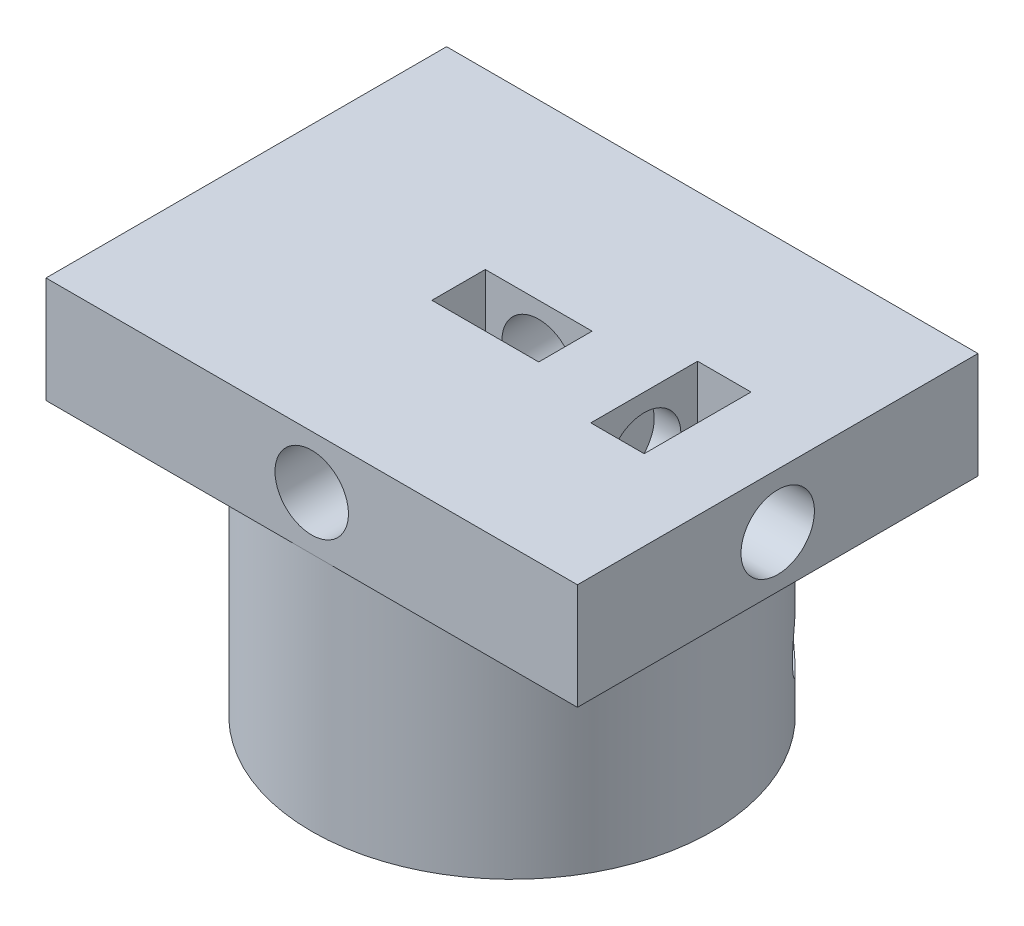
SolidWorks part; units mm, degrees
material "ONYX"
ref_plane "Front Plane" through (0, 0, 0) normal (0, 0, 1) x (1, 0, 0)
ref_plane "Top Plane" through (0, 0, 0) normal (0, 1, 0) x (1, 0, 0)
ref_plane "Right Plane" through (0, 0, 0) normal (1, 0, 0) x (0, 0, -1)
sketch "Sketch1" plane through (0, 0, 0) normal (0, 1, 0) x (1, 0, 0)
  circle A0 centre (0, 0) radius 4.5
  circle A1 centre (0, 0) radius 15
  dimension "D1" = 9
  dimension "D2" = 30
extrude "Boss-Extrude1" add sketch "Sketch1" along normal mid plane 18
sketch "Sketch2" plane through (0, 9, 0) normal (0, 1, 0) x (1, 0, 0)
  line L1 (19.9, -15) -> (-19.9, -15)
  line L2 (19.9, -15) -> (19.9, 15)
  line L3 (19.9, 15) -> (-19.9, 15)
  line L4 (-19.9, -15) -> (-19.9, 15)
  line L5 (19.9, -15) -> (-19.9, 15) construction
  line L6 (19.9, 15) -> (-19.9, -15) construction
  point P0 (0, 0)
  dimension "D1" = 30
  dimension "D2" = 39.8
extrude "Boss-Extrude2" add sketch "Sketch2" along normal blind 7.95
sketch "Sketch3" plane through (0, 0, -15) normal (0, 0, -1) x (-1, 0, 0)
  line L1 (-19.9, 12.975) -> (19.9, 12.975) construction
  line L2 (19.9, 16.95) -> (19.9, 9) construction
  line L3 (-19.9, 16.95) -> (-19.9, 9) construction
  line L4 (0, 16.95) -> (0, 9) construction
  line L5 (-19.9, 16.95) -> (19.9, 16.95) construction
  circle A0 centre (0, 12.975) radius 2.75
  dimension "D3" = 5.5
ref_plane "Plane1" through (0, 0, 0) normal (0.7071, 0, -0.7071) x (-0.7071, 0, -0.7071)
ref_plane "Plane2" through (0, 0, 0) normal (0.7071, 0, 0.7071) x (0.7071, 0, -0.7071)
ref_plane "Plane4" through (10.6066, 0, -10.6066) normal (0.7071, 0, -0.7071) x (-0.7071, 0, -0.7071)
sketch "Sketch18" plane through (10.6066, 0, -10.6066) normal (0.7071, 0, -0.7071) x (-0.7071, 0, -0.7071)
  line L0 (0, -9) -> (0, 9) construction
  line L2 (-15, -9) -> (15, -9) construction
  line L5 (-15, 9) -> (10.6066, 9) construction
hole_wizard "M5 Tapped Hole1" positions "Sketch22" profile "Sketch24" tap size "M5" standard "DIN"
sketch "Sketch22" plane through (10.6066, 0, -10.6066) normal (0.7071, 0, -0.7071) x (-0.7071, 0, -0.7071)
  line L0 (0, -9) -> (0, 9) construction
  point P0 (0, -4)
  dimension "D1" = 13
sketch "Sketch24" plane through (10.6066, -4, -10.6066) normal (0, 1, 0) x (-0.7071, 0, -0.7071)
  line L0 (0, 0) -> (0, 10.5)
  line L1 (0, 10.5) -> (2.1, 10.5)
  line L2 (2.1, 10.5) -> (2.1, 0)
  line L5 (2.1, 0) -> (0, 0)
  line L11 (0, -6.35) -> (0, 107.95) construction
  dimension "Thru Tap Drill Dia." = 4.2
  dimension "Thru Tap Drill Depth" = 10.5
cosmetic thread "Hole Thread1"
thread "Thread1" pitch 0.8 start angle 0, offset 0, length 12, pitch 0.8, diameter 4.2
ref_plane "Plane5" through (12.0915, -4, -9.1217) normal (0, -1, 0) x (0.7071, 0, 0.7071)
sketch "Thread Profile2" plane through (12.0915, -4, -9.1217) normal (0, -1, 0) x (0.7071, 0, 0.7071)
  line L0 (0, 0) -> (0, 0.8) construction
  line L1 (0, 0) -> (0.433, 0.25)
  line L2 (0.433, 0.25) -> (0.433, 0.35)
  line L3 (0.433, 0.35) -> (0, 0.6)
  line L4 (0.433, 0.3) -> (0, 0.3) construction
  line L11 (0, 0) -> (0, 0.6)
  point P2 (0, 0)
  dimension "Pitch" = 0.8
  dimension "Profile_Angle" = 60
  dimension "Profile_Land" = 0.1
  dimension "Profile_Height" = 0.433
ref_plane "Plane6" through (-10.6066, 0, -10.6066) normal (-0.7071, 0, -0.7071) x (-0.7071, 0, 0.7071)
sketch "Sketch29" plane through (-10.6066, 0, -10.6066) normal (-0.7071, 0, -0.7071) x (-0.7071, 0, 0.7071)
  line L0 (0, -9) -> (0, 9) construction
  line L1 (-15, -9) -> (15, -9) construction
  line L2 (-10.6066, 9) -> (15, 9) construction
hole_wizard "M5 Tapped Hole2" positions "Sketch31" profile "Sketch32" tap size "M5" standard "DIN"
sketch "Sketch31" plane through (-10.6066, 0, -10.6066) normal (-0.7071, 0, -0.7071) x (-0.7071, 0, 0.7071)
  line L0 (0, -9) -> (0, 9) construction
  point P0 (0, -4)
  dimension "D1" = 13
sketch "Sketch32" plane through (-10.6066, -4, -10.6066) normal (0, 1, 0) x (-0.7071, 0, 0.7071)
  line L0 (0, 0) -> (0, 10.5)
  line L1 (0, 10.5) -> (2.1, 10.5)
  line L2 (2.1, 10.5) -> (2.1, 0)
  line L5 (2.1, 0) -> (0, 0)
  line L11 (0, -6.35) -> (0, 107.95) construction
  dimension "Thru Tap Drill Dia." = 4.2
  dimension "Thru Tap Drill Depth" = 10.5
cosmetic thread "Hole Thread2"
thread "Thread2" pitch 0.8 start angle 0, offset 0, length 12, pitch 0.8, diameter 4.2
ref_plane "Plane7" through (-9.1217, -4, -12.0915) normal (0, -1, 0) x (0.7071, 0, -0.7071)
sketch "Thread Profile3" plane through (-9.1217, -4, -12.0915) normal (0, -1, 0) x (0.7071, 0, -0.7071)
  line L0 (0, 0) -> (0, 0.8) construction
  line L1 (0, 0) -> (0.433, 0.25)
  line L2 (0.433, 0.25) -> (0.433, 0.35)
  line L3 (0.433, 0.35) -> (0, 0.6)
  line L4 (0.433, 0.3) -> (0, 0.3) construction
  line L11 (0, 0) -> (0, 0.6)
  point P2 (0, 0)
  dimension "Pitch" = 0.8
  dimension "Profile_Angle" = 60
  dimension "Profile_Land" = 0.1
  dimension "Profile_Height" = 0.433
sketch "Sketch33" plane through (0, 0, 0) normal (1, 0, 0) x (0, 0, -1)
  line L0 (0, 0) -> (0, 200) construction
  dimension "D1" = 200
sketch "Sketch34" plane through (0, 0, 15) normal (0, 0, 1) x (1, 0, 0)
  line L0 (-19.9, 12.75) -> (19.9, 12.75) construction
  line L1 (-19.9, 16.95) -> (-19.9, 9) construction
  line L2 (19.9, 16.95) -> (19.9, 9) construction
  line L3 (0, 9) -> (19.9, 9) construction
  circle A0 centre (0, 12.75) radius 1.5
  dimension "D2" = 3
  dimension "D1" = 3.75
extrude "Cut-Extrude1" cut sketch "Sketch3" against normal through all
sketch "Sketch35" plane through (0, 16.95, 0) normal (0, 1, 0) x (1, 0, 0)
  line L0 (0, 0) -> (19.9, 0) construction
  line L1 (4, -2) -> (-4, -2)
  line L2 (4, -2) -> (4, 2)
  line L3 (4, 2) -> (-4, 2)
  line L4 (-4, -2) -> (-4, 2)
  line L5 (4, -2) -> (-4, 2) construction
  line L6 (4, 2) -> (-4, -2) construction
  line L7 (19.9, -15) -> (19.9, 15) construction
  line L9 (13.9, -4) -> (9.9, -4)
  line L10 (13.9, -4) -> (13.9, 4)
  line L11 (13.9, 4) -> (9.9, 4)
  line L12 (9.9, -4) -> (9.9, 4)
  line L13 (13.9, -4) -> (9.9, 4) construction
  line L14 (13.9, 4) -> (9.9, -4) construction
  point P0 (0, 0)
  point P10 (11.9, 0)
  dimension "D1" = 4
  dimension "D2" = 8
  dimension "D3" = 4
  dimension "D4" = 8
  dimension "D5" = 8
extrude "Cut-Extrude4" cut sketch "Sketch35" against normal blind 8 contours L3 L4 L1 L2 | L10 L9 L12 L11
sketch "Sketch40" plane through (19.9, 0, 0) normal (1, 0, 0) x (0, 0, -1)
  line L0 (-15, 12.75) -> (15, 12.975) construction
  line L1 (-15, 14.25) -> (-15, 11.25) construction
  line L2 (15, 16.95) -> (15, 9) construction
  line L3 (0, 16.95) -> (0, 9) construction
  line L4 (-15, 16.95) -> (15, 16.95) construction
  line L5 (-15, 9) -> (15, 9) construction
  circle A0 centre (0, 12.8625) radius 2.75
  dimension "D1" = 5.5
extrude "Cut-Extrude5" cut sketch "Sketch40" against normal blind 12
